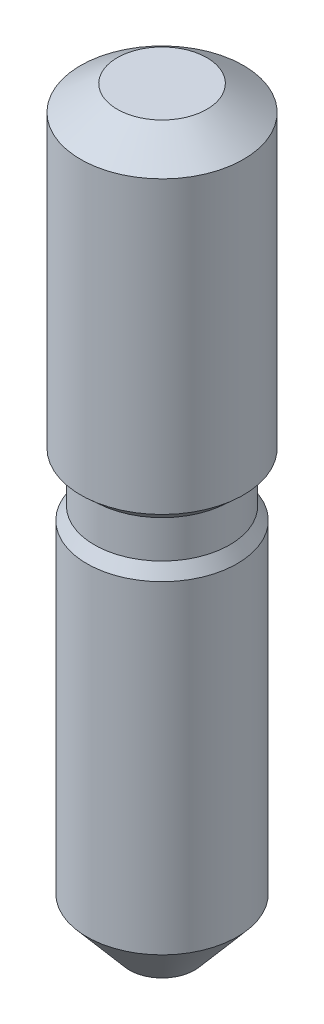
SolidWorks part; units mm, degrees
ref_plane "Alzado" through (0, 0, 0) normal (0, 0, 1) x (1, 0, 0)
ref_plane "Planta" through (0, 0, 0) normal (0, 1, 0) x (1, 0, 0)
ref_plane "Vista lateral" through (0, 0, 0) normal (1, 0, 0) x (0, 0, -1)
sketch "Sketch1" plane through (0, 0, 0) normal (0, 0, 1) x (1, 0, 0)
  line L0 (0, 0) -> (3.575, 0)
  line L1 (3.575, 0) -> (6.5, -2)
  line L2 (6.5, -2) -> (6.5, -25.2)
  line L3 (6.5, -25.2) -> (5.4, -26.2)
  line L4 (5.4, -26.2) -> (5.4, -29.2)
  line L5 (5.4, -29.2) -> (6, -30.2)
  line L6 (6, -30.2) -> (6, -56)
  line L7 (6, -56) -> (2.6, -60)
  line L8 (2.6, -60) -> (0, -60)
  line L9 (0, -60) -> (0, 0)
  line L10 (0, -64) -> (0, 4) construction
revolve "Motor_reductora_husillo" add sketch "Sketch1" angle 360 about L10
